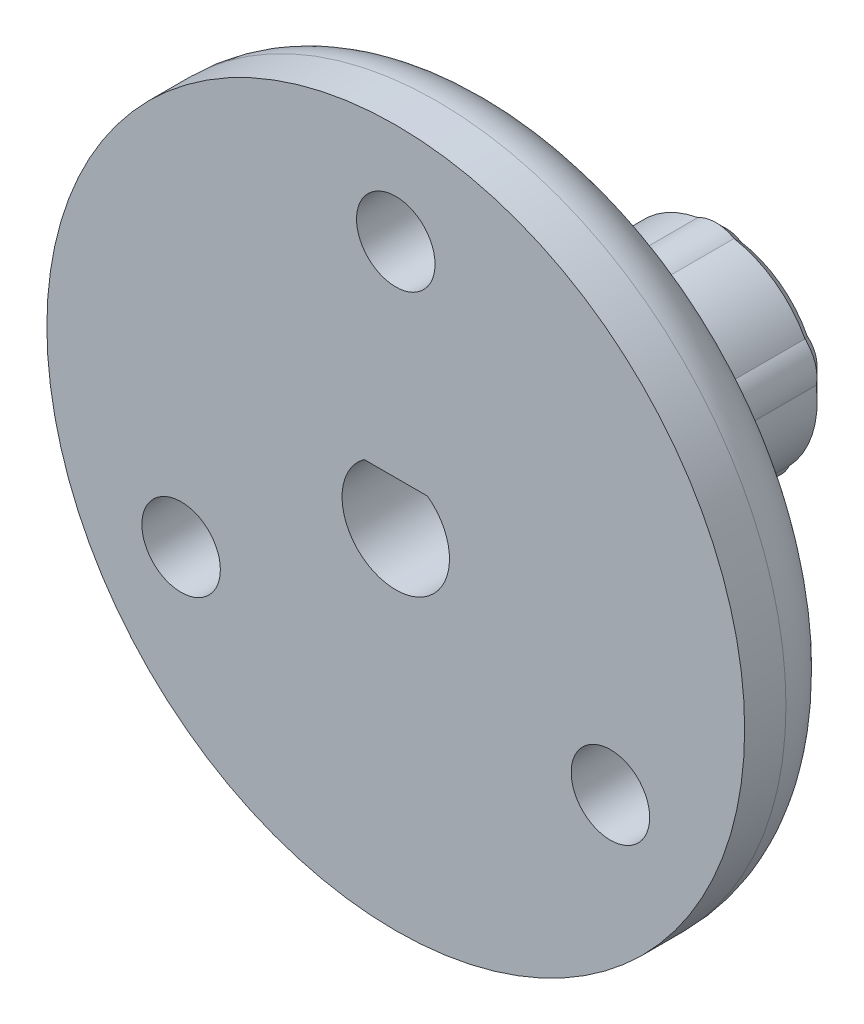
SolidWorks part; units mm, degrees
ref_plane "Ebene vorne" through (0, 0, 0) normal (0, 0, 1) x (1, 0, 0)
ref_plane "Ebene oben" through (0, 0, 0) normal (0, 1, 0) x (1, 0, 0)
ref_plane "Ebene rechts" through (0, 0, 0) normal (1, 0, 0) x (0, 0, -1)
sketch "Skizze3" plane through (0, 0, 0) normal (0, 0, 1) x (1, 0, 0)
  line L0 (0, 0) -> (0, 3.25) construction
  circle A0 centre (0, 0) radius 4.9
  circle A1 centre (0, 0) radius 5.05 construction
  circle A2 centre (0, 3.25) radius 1.8
  circle A3 centre (3.0909, 1.0043) radius 1.8
  circle A4 centre (1.9103, -2.6293) radius 1.8
  circle A5 centre (-1.9103, -2.6293) radius 1.8
  circle A6 centre (-3.0909, 1.0043) radius 1.8
  point P7 (3.0605, -2.5601)
  point P8 (0, 0)
  point P16 (0, 0)
  dimension "D1" = 9.8
  dimension "D2" = 10.1
  dimension "D3" = 3.6
  dimension "D4" = 5
extrude "Aufsatz-Linear austragen1" add sketch "Skizze3" along normal blind 16 contours A6 A0 A5 A4 A3 A2 | A0 A2 | A0 A6 | A0 A3 | A0 A4 | A0 A5 | A0 A6 | A0 A2 | A0 A4 | A0 A5 | A0 A3
sketch "Skizze4" plane through (0, 0, 0) normal (0, 0, -1) x (-1, 0, 0)
  line L0 (-1.533, 2.1) -> (1.533, 2.1)
  arc A0 (-1.533, 2.1) -> (1.533, 2.1) centre (0, 0) ccw
  point P1 (0, 0)
  point P5 (0.1561, -1.0243)
  point P6 (0, 0)
  dimension "D1" = 5.2
  dimension "D2" = 4.7
extrude "Schnitt-Linear austragen1" cut sketch "Skizze4" against normal up to surface (16 mm away) up to face at (0, 0, 16)
sketch "Skizze5" plane through (0, 0, 0) normal (0, 1, 0) x (1, 0, 0)
  line L0 (-0.8797, 0) -> (-4.3126, 0) construction
  line L18 (-4.8909, -16) -> (-16.8909, -16)
  line L19 (-16.8909, -16) -> (-16.8909, -11)
  line L20 (-16.8909, -11) -> (-6.8909, -11)
  line L21 (-6.8909, -11) -> (-6.8909, -8)
  line L22 (-6.8909, -8) -> (-4.8909, -8)
  line L23 (-4.8909, -8) -> (-4.8909, -16)
  point P1 (-5.4026, -15.0594)
  point P4 (0, 0)
  point P8 (-4.8909, -14.8526)
  dimension "D1" = 8
  dimension "D2" = 12
  dimension "D3" = 2
  dimension "D4" = 5
revolve "Rotation1" add sketch "Skizze5" angle 360 about axis through (0, 0, 16) along (0, 0, -1)
fillet "Verrundung3" radius 3 1 edges at (16.8909, 0, 11)
sketch "Skizze6" plane through (0, 0, 16) normal (0, 0, 1) x (1, 0, 0)
  line L0 (0, 0) -> (0, 12) construction
  circle A0 centre (0, 12) radius 1.9
  dimension "D1" = 3.8
  dimension "D2" = 12
extrude "Schnitt-Linear austragen2" cut sketch "Skizze6" against normal blind 4.5
pattern_circular "Kreismuster1" count 3 over 360 about axis through (0, 0, 0) along (0, 0, 1) of "Schnitt-Linear austragen2"
chamfer "Fase1" distance 0.5 angle 45 10 edges at (0, 5.05, 0) (2.8801, 3.9642, 0) (4.8028, 1.5605, 0) (4.6602, -1.5142, 0) (2.9683, -4.0855, 0) (0, -4.9, 0) (-2.9683, -4.0855, 0) (-4.6602, -1.5142, 0) (-4.8028, 1.5605, 0) (-2.8801, 3.9642, 0)
